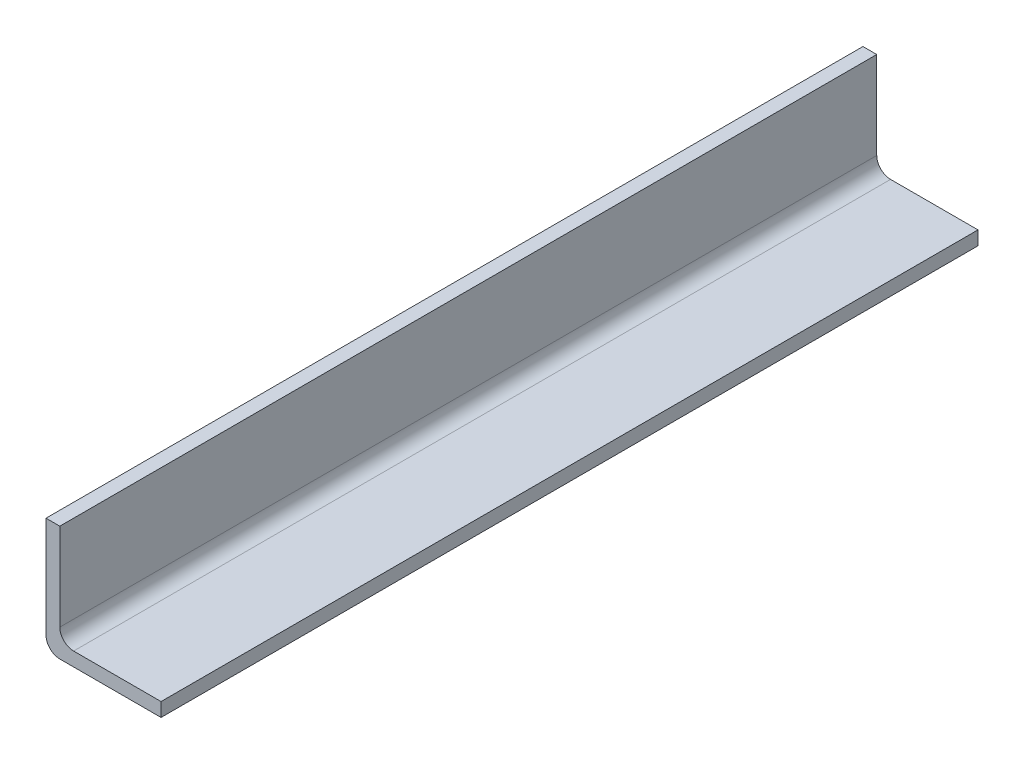
SolidWorks part; units mm, degrees
ref_plane "Front Plane" through (0, 0, 0) normal (0, 0, 1) x (1, 0, 0)
ref_plane "Top Plane" through (0, 0, 0) normal (0, 1, 0) x (1, 0, 0)
ref_plane "Right Plane" through (0, 0, 0) normal (1, 0, 0) x (0, 0, -1)
sketch "Sketch1" plane through (0, 0, 0) normal (0, 0, 1) x (1, 0, 0)
  line L0 (0, 0) -> (0, 50)
  line L1 (0, 0) -> (50, 0)
  line L2 (6, 6) -> (50, 6)
  line L3 (6, 6) -> (6, 50)
  line L4 (0, 50) -> (6, 50)
  line L5 (50, 6) -> (50, 0)
  dimension "D1" = 50
  dimension "D2" = 6
extrude "Boss-Extrude1" add sketch "Sketch1" along normal blind 355
fillet "Fillet1" radius 6 2 edges at (6, 6, 177.5) (0, 0, 177.5)
equation "\"rearLightHeight_para\"=265.0"
equation "\"D1@Boss-Extrude1\" = \"rearLightHeight_para\" + 90"
equation "\"CarBeamWidth\"=700.0"
equation "\"WheelWidth\"=650.0"
equation "\"Wheel_FrontBoxDistance\"=1390.0"
equation "\"MetalSheet_3mm_length\"=5030.0"
equation "\"MetalSheet_3mm_width\"=1923.0"
equation "\"MetalSheet_3mm_FloorCut_L_length\"=1764.0"
equation "\"MetalSheet_3mm_FloorCut_L_disdance\"=1665.0"
equation "\"MetalSheet_3mm_FloorCut_R_length\"=1764.0"
equation "\"MetalSheet_3mm_FloorCut_R_disdance\"=1665.0"
equation "\"indoorHeight\"=1940.0"
equation "\"indoorHeight_para\"=25.0"
equation "\"haveDoor_R\"=1"
equation "\"side_door_bottom_R_3mm_length\"=1934.0"
equation "\"side_door_bottom_R_3mm_toFrontDistance\"=1583.0"
equation "\"1Bar_Side_RF_3mm_length\"=1493.0"
equation "\"1Bar_Side_RB_3mm_length\"=1493.0"
equation "\"DoorSeparator_RF_3mm_withHinge_toFrontDistance\"=1673.0"
equation "\"DoorSeparator_RF_3mm_withHinge_exist\"=1"
equation "\"DoorSeparator_RB_3mm_withHinge_toFrontDistance\"=3427.0"
equation "\"DoorSeparator_RB_3mm_withHinge_exist\"=1"
equation "\"Door_R1_L_open_Single_toFrontDistance\"=2547.5"
equation "\"Door_R1_L_open_Single_exist\"=1"
equation "\"door_base_long7_R1_L_open_Single_height\"=1890.0"
equation "\"door_base_short7_R1_L_open_Single_height\"=1890.0"
equation "\"door_base_short7_R1_L_open_Single_width\"=864"
equation "\"Door_R1_R_open_Single_toFrontDistance\"=3422.0"
equation "\"Door_R1_R_open_Single_exist\"=1"
equation "\"door_base_long7_R1_R_open_Single_height\"=1890.0"
equation "\"door_base_short7_R1_R_open_Single_height\"=1890.0"
equation "\"door_base_short7_R1_R_open_Single_width\"=864"
equation "\"x\"=66.0"
equation "\"da\"=62.0"
equation "\"SquareTube_length\"=1923.0"
equation "\"channelSteel_length\"=5030.0"
equation "\"SquareTube_inFront_AvgDistance\"=285.0"
equation "\"SquareTube_inFront_TotalCount\"=5"
equation "\"SquareTube_inFront1_cutDepth50_R\"=0.5"
equation "\"SquareTube_inFront1_cutDepth50_L\"=0.5"
equation "\"SquareTube_inFront2_cutDepth50_R\"=0.5"
equation "\"SquareTube_inFront2_cutDepth50_L\"=0.5"
equation "\"SquareTube_inFront3_cutDepth50_R\"=0.5"
equation "\"SquareTube_inFront3_cutDepth50_L\"=0.5"
equation "\"SquareTube_inFront4_cutDepth50_R\"=0.5"
equation "\"SquareTube_inFront4_cutDepth50_L\"=0.5"
equation "\"SquareTube_inFront5_cutDepth50_R\"=50"
equation "\"SquareTube_inFront5_cutDepth50_L\"=50"
equation "\"SquareTube_inFront6_cutDepth50_R\"=50"
equation "\"SquareTube_inFront6_cutDepth50_L\"=50"
equation "\"SquareTube_inFront7_cutDepth50_R\"=50"
equation "\"SquareTube_inFront7_cutDepth50_L\"=50"
equation "\"SquareTube_inFront8_cutDepth50_R\"=50"
equation "\"SquareTube_inFront8_cutDepth50_L\"=50"
equation "\"SquareTube_inFront9_cutDepth50_R\"=50"
equation "\"SquareTube_inFront9_cutDepth50_L\"=50"
equation "\"SquareTube_inFront10_cutDepth50_R\"=50"
equation "\"SquareTube_inFront10_cutDepth50_L\"=50"
equation "\"SquareTube_inFront11_cutDepth50_R\"=50"
equation "\"SquareTube_inFront11_cutDepth50_L\"=50"
equation "\"SquareTube_inFront12_cutDepth50_R\"=50"
equation "\"SquareTube_inFront12_cutDepth50_L\"=50"
equation "\"SquareTube_inFront13_cutDepth50_R\"=50"
equation "\"SquareTube_inFront13_cutDepth50_L\"=50"
equation "\"SquareTube_inFront14_cutDepth50_R\"=50"
equation "\"SquareTube_inFront14_cutDepth50_L\"=50"
equation "\"SquareTube_inBack_AvgDistance\"=333.125"
equation "\"SquareTube_inBack_TotalCount\"=9"
equation "\"SquareTube_inBack1_cutDepth50_R\"=50"
equation "\"SquareTube_inBack1_cutDepth50_L\"=50"
equation "\"SquareTube_inBack2_cutDepth50_R\"=50"
equation "\"SquareTube_inBack2_cutDepth50_L\"=50"
equation "\"SquareTube_inBack3_cutDepth50_R\"=50"
equation "\"SquareTube_inBack3_cutDepth50_L\"=50"
equation "\"SquareTube_inBack4_cutDepth50_R\"=50"
equation "\"SquareTube_inBack4_cutDepth50_L\"=50"
equation "\"SquareTube_inBack5_cutDepth50_R\"=50"
equation "\"SquareTube_inBack5_cutDepth50_L\"=50"
equation "\"SquareTube_inBack6_cutDepth50_R\"=0.5"
equation "\"SquareTube_inBack6_cutDepth50_L\"=0.5"
equation "\"SquareTube_inBack7_cutDepth50_R\"=0.5"
equation "\"SquareTube_inBack7_cutDepth50_L\"=0.5"
equation "\"SquareTube_inBack8_cutDepth50_R\"=0.5"
equation "\"SquareTube_inBack8_cutDepth50_L\"=0.5"
